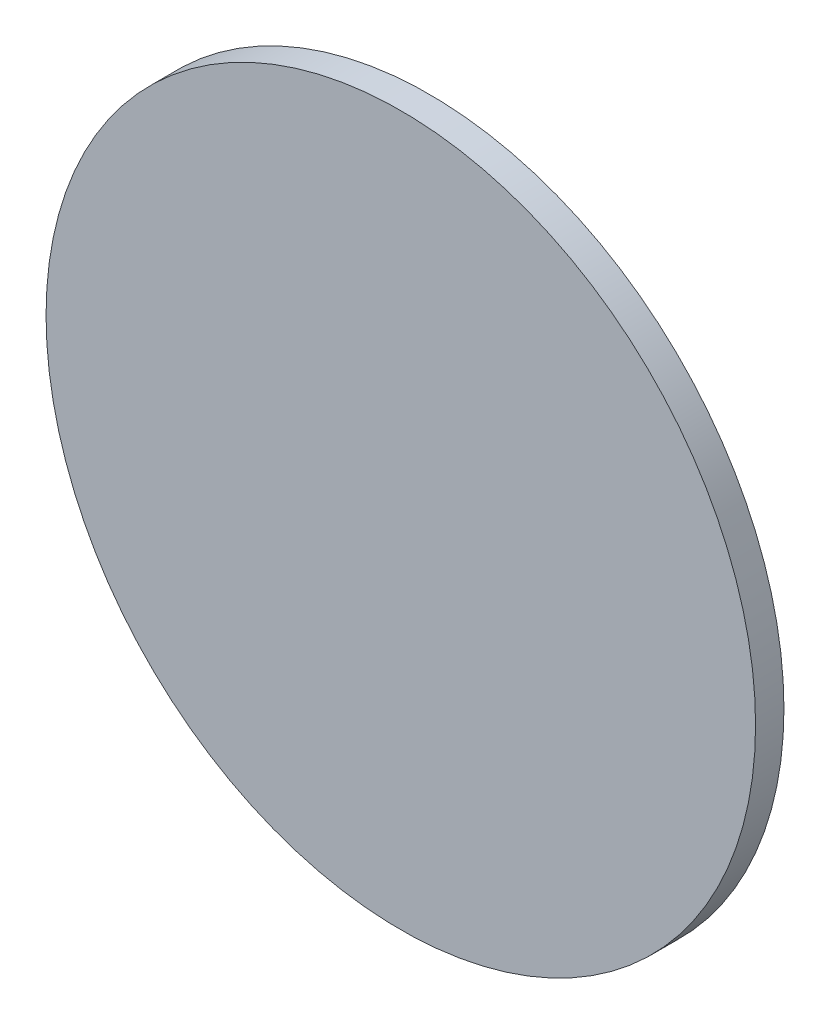
SolidWorks part; units mm, degrees
ref_plane "Спереди" through (0, 0, 0) normal (0, 0, 1) x (1, 0, 0)
ref_plane "Сверху" through (0, 0, 0) normal (0, 1, 0) x (1, 0, 0)
ref_plane "Справа" through (0, 0, 0) normal (1, 0, 0) x (0, 0, -1)
sketch "Эскиз1" plane through (0, 0, 0) normal (0, 0, 1) x (1, 0, 0)
  circle A0 centre (0, 0) radius 50
  dimension "D1" = 100
extrude "Бобышка-Вытянуть1" add sketch "Эскиз1" along normal blind 4
sketch "Эскиз2" plane through (0, 0, 0) normal (0, 0, -1) x (-1, 0, 0)
  line L0 (0, 0) -> (0, 8.4464) construction
  point P2 (0, 0)
  point P4 (0, 0)
  point P5 (0, 8.4464)
  line B0 (26, 8.4464) -> (-26, 8.4464) construction
  line B1 (26, -17.5536) -> (-26, -17.5536) construction
  line B2 (22, -43.5536) -> (-22, -43.5536)
  line B3 (26, -39.5536) -> (26, 4.4464)
  line B4 (22, 8.4464) -> (-22, 8.4464)
  line B5 (-26, -39.5536) -> (-26, 4.4464)
  line B6 (0, -43.5536) -> (0, 8.4464) construction
  line B7 (-19.2, -3.5536) -> (-16.8, -3.5536)
  line B8 (5.6, -11.5536) -> (-5.6, -11.5536)
  line B9 (8, -13.9536) -> (8, -21.1536)
  line B10 (5.6, -23.5536) -> (-5.6, -23.5536)
  line B11 (-8, -13.9536) -> (-8, -21.1536)
  line B12 (8, -11.5536) -> (-8, -23.5536) construction
  line B13 (8, -23.5536) -> (-8, -11.5536) construction
  line B14 (14.4, -13.5536) -> (9.6, -13.5536)
  line B15 (15.2, -14.3536) -> (15.2, -20.7536)
  line B16 (14.4, -21.5536) -> (9.6, -21.5536)
  line B17 (8.8, -14.3536) -> (8.8, -20.7536)
  line B18 (15.2, -13.5536) -> (8.8, -21.5536) construction
  line B19 (15.2, -21.5536) -> (8.8, -13.5536) construction
  line B20 (19.2, -3.5536) -> (16.8, -3.5536)
  line B21 (20, -4.3536) -> (20, -30.7536)
  line B22 (19.2, -31.5536) -> (16.8, -31.5536)
  line B23 (16, -4.3536) -> (16, -30.7536)
  line B24 (20, -3.5536) -> (16, -31.5536) construction
  line B25 (20, -31.5536) -> (16, -3.5536) construction
  line B26 (-20, -4.3536) -> (-20, -30.7536)
  line B27 (-19.2, -31.5536) -> (-16.8, -31.5536)
  line B28 (-16, -4.3536) -> (-16, -30.7536)
  line B29 (-14.4, -13.5536) -> (-9.6, -13.5536)
  line B30 (-15.2, -14.3536) -> (-15.2, -20.7536)
  line B31 (-14.4, -21.5536) -> (-9.6, -21.5536)
  line B32 (-8.8, -14.3536) -> (-8.8, -20.7536)
  line B33 (-2.8, -30.3536) -> (-6.8, -30.3536) construction
  line B34 (1.2, -28.3536) -> (-1.2, -28.3536)
  line B35 (2, -27.5536) -> (2, -25.1536)
  line B36 (1.2, -24.3536) -> (-1.2, -24.3536)
  line B37 (-2, -27.5536) -> (-2, -25.1536)
  line B38 (2, -28.3536) -> (-2, -24.3536) construction
  line B39 (2, -24.3536) -> (-2, -28.3536) construction
  line B40 (1.2, -31.5536) -> (-1.2, -31.5536)
  line B41 (2, -30.7536) -> (2, -29.9536)
  line B42 (1.2, -29.1536) -> (-1.2, -29.1536)
  line B43 (-2, -30.7536) -> (-2, -29.9536)
  line B44 (2, -31.5536) -> (-2, -29.1536) construction
  line B45 (2, -29.1536) -> (-2, -31.5536) construction
  line B46 (-6.8, -30.3536) -> (-13.7282, -34.3536) construction
  line B47 (-13.7282, -34.3536) -> (-14.5282, -34.3536) construction
  line B48 (-2.8, -29.9536) -> (-6.6928, -29.9536)
  line B49 (-7.0928, -30.0608) -> (-13.6497, -33.8464)
  line B50 (-14.0497, -33.9536) -> (-14.5282, -33.9536)
  line B51 (-2.8, -30.7536) -> (-6.4785, -30.7536)
  line B52 (-6.8785, -30.8608) -> (-13.4354, -34.6464)
  line B53 (-13.8354, -34.7536) -> (-14.5282, -34.7536)
  line B54 (-2.8, -29.9536) -> (-2.8, -30.7536)
  line B55 (-14.5282, -34.7536) -> (-14.5282, -33.9536)
  line B56 (-15.3282, -33.7536) -> (-23.3282, -33.7536)
  line B57 (-15.3282, -33.7536) -> (-15.3282, -34.9536)
  line B58 (-15.3282, -34.9536) -> (-23.3282, -34.9536)
  line B59 (-23.3282, -33.7536) -> (-23.3282, -34.9536)
  line B60 (-15.3282, -33.7536) -> (-23.3282, -34.9536) construction
  line B61 (-15.3282, -34.9536) -> (-23.3282, -33.7536) construction
  arc B62 (26, 4.4464) -> (22, 8.4464) centre (22, 4.4464) ccw
  arc B63 (-22, 8.4464) -> (-26, 4.4464) centre (-22, 4.4464) ccw
  arc B64 (-22, -43.5536) -> (-26, -39.5536) centre (-22, -39.5536) cw
  arc B65 (22, -43.5536) -> (26, -39.5536) centre (22, -39.5536) ccw
  arc B66 (5.6, -11.5536) -> (8, -13.9536) centre (5.6, -13.9536) cw
  arc B67 (-5.6, -11.5536) -> (-8, -13.9536) centre (-5.6, -13.9536) ccw
  arc B68 (-5.6, -23.5536) -> (-8, -21.1536) centre (-5.6, -21.1536) cw
  arc B69 (8, -21.1536) -> (5.6, -23.5536) centre (5.6, -21.1536) cw
  arc B70 (9.6, -13.5536) -> (8.8, -14.3536) centre (9.6, -14.3536) ccw
  arc B71 (14.4, -13.5536) -> (15.2, -14.3536) centre (14.4, -14.3536) cw
  arc B72 (15.2, -20.7536) -> (14.4, -21.5536) centre (14.4, -20.7536) cw
  arc B73 (9.6, -21.5536) -> (8.8, -20.7536) centre (9.6, -20.7536) cw
  arc B74 (16.8, -3.5536) -> (16, -4.3536) centre (16.8, -4.3536) ccw
  arc B75 (19.2, -3.5536) -> (20, -4.3536) centre (19.2, -4.3536) cw
  arc B76 (16.8, -31.5536) -> (16, -30.7536) centre (16.8, -30.7536) cw
  arc B77 (20, -30.7536) -> (19.2, -31.5536) centre (19.2, -30.7536) cw
  arc B78 (-16.8, -3.5536) -> (-16, -4.3536) centre (-16.8, -4.3536) cw
  arc B79 (-19.2, -3.5536) -> (-20, -4.3536) centre (-19.2, -4.3536) ccw
  arc B80 (-20, -30.7536) -> (-19.2, -31.5536) centre (-19.2, -30.7536) ccw
  arc B81 (-16.8, -31.5536) -> (-16, -30.7536) centre (-16.8, -30.7536) ccw
  arc B82 (-9.6, -13.5536) -> (-8.8, -14.3536) centre (-9.6, -14.3536) cw
  arc B83 (-14.4, -13.5536) -> (-15.2, -14.3536) centre (-14.4, -14.3536) ccw
  arc B84 (-15.2, -20.7536) -> (-14.4, -21.5536) centre (-14.4, -20.7536) ccw
  arc B85 (-9.6, -21.5536) -> (-8.8, -20.7536) centre (-9.6, -20.7536) ccw
  arc B86 (2, -25.1536) -> (1.2, -24.3536) centre (1.2, -25.1536) ccw
  arc B87 (-1.2, -24.3536) -> (-2, -25.1536) centre (-1.2, -25.1536) ccw
  arc B88 (-1.2, -28.3536) -> (-2, -27.5536) centre (-1.2, -27.5536) cw
  arc B89 (1.2, -28.3536) -> (2, -27.5536) centre (1.2, -27.5536) ccw
  arc B90 (-1.2, -29.1536) -> (-2, -29.9536) centre (-1.2, -29.9536) ccw
  arc B91 (-1.2, -31.5536) -> (-2, -30.7536) centre (-1.2, -30.7536) cw
  arc B92 (1.2, -31.5536) -> (2, -30.7536) centre (1.2, -30.7536) ccw
  arc B93 (2, -29.9536) -> (1.2, -29.1536) centre (1.2, -29.9536) ccw
  arc B94 (-13.6497, -33.8464) -> (-14.0497, -33.9536) centre (-14.0497, -33.1536) cw
  arc B95 (-13.4354, -34.6464) -> (-13.8354, -34.7536) centre (-13.8354, -33.9536) cw
  arc B96 (-6.4785, -30.7536) -> (-6.8785, -30.8608) centre (-6.4785, -31.5536) ccw
  arc B97 (-6.6928, -29.9536) -> (-7.0928, -30.0608) centre (-6.6928, -30.7536) ccw
sketch_block_instance "Блок1-1"
sketch_block "Блок1" parameters "D1"=0.5, "D10"=0.3, "D11"=0.1, "D12"=0.1, "D16"=0.1, "D20"=0.1, "D31"=0.1, "D2"=1.5, "D3"=2, "D4"=0.8, "D5"=1, "D6"=0.1, "D7"=3.5, "D8"=0.5, "D9"=0.1, "D13"=0.1, "D14"=0.5, "D15"=0.5, "D17"=0.5, "D18"=0.3, "D19"=0.1, "D21"=0.5, "D22"=0.1, "D23"=30, "D24"=0.1, "D25"=0.5, "D26"=1.55, "D27"=0.1, "D28"=0.1, "D29"=0.15, "D30"=1, "D32"=6.5
extrude "Вырез-Вытянуть1" cut sketch "Эскиз2" against normal blind 0.2 contours B73 B16 B72 B15 B71 B14 B70 B17 | B69 B9 B66 B8 B67 B11 B68 B10 | B31 B85 B32 B82 B29 B83 B30 B84 | B77 B21 B75 B20 B74 B23 B76 B22 | B27 B81 B28 B78 B7 B79 B26 B80 | B56 B59 B58 B57 | B48 B97 B49 B94 B50 B55 B53 B95 B52 B96 B51 B54 | B34 B89 B35 B86 B36 B87 B37 B88 | B41 B93 B42 B90 B43 B91 B40 B92
sketch "Эскиз3" plane through (0, 0, 0) normal (0, 0, -1) x (-1, 0, 0)
  line L0 (45.8258, 20) -> (-45.8258, 20) construction
  line L1 (0, 20) -> (0, 0) construction
  circle A0 centre (0, 0) radius 50 construction
  text T0 "<b>BREEZE</b>" font "Arial Narrow" height 15
  point P3 (0, 0)
  point P4 (0, 0)
  point P6 (0, 21.8911)
  point P8 (42.5312, 20)
  point P9 (45.8258, 20)
  point P12 (-45.8258, 20)
  dimension "D1" = 20
sketch "Эскиз4" plane through (0, 0, 0) normal (0, 0, -1) x (-1, 0, 0)
  circle A0 centre (0, 0) radius 47
  circle A1 centre (0, 0) radius 45
  circle A2 centre (0, 0) radius 50 construction
  dimension "D1" = 3
  dimension "D2" = 2
extrude "Вырез-Вытянуть2" cut sketch "Эскиз4" against normal blind 0.2
extrude "Вырез-Вытянуть3" cut sketch "Эскиз3" against normal blind 0.2
